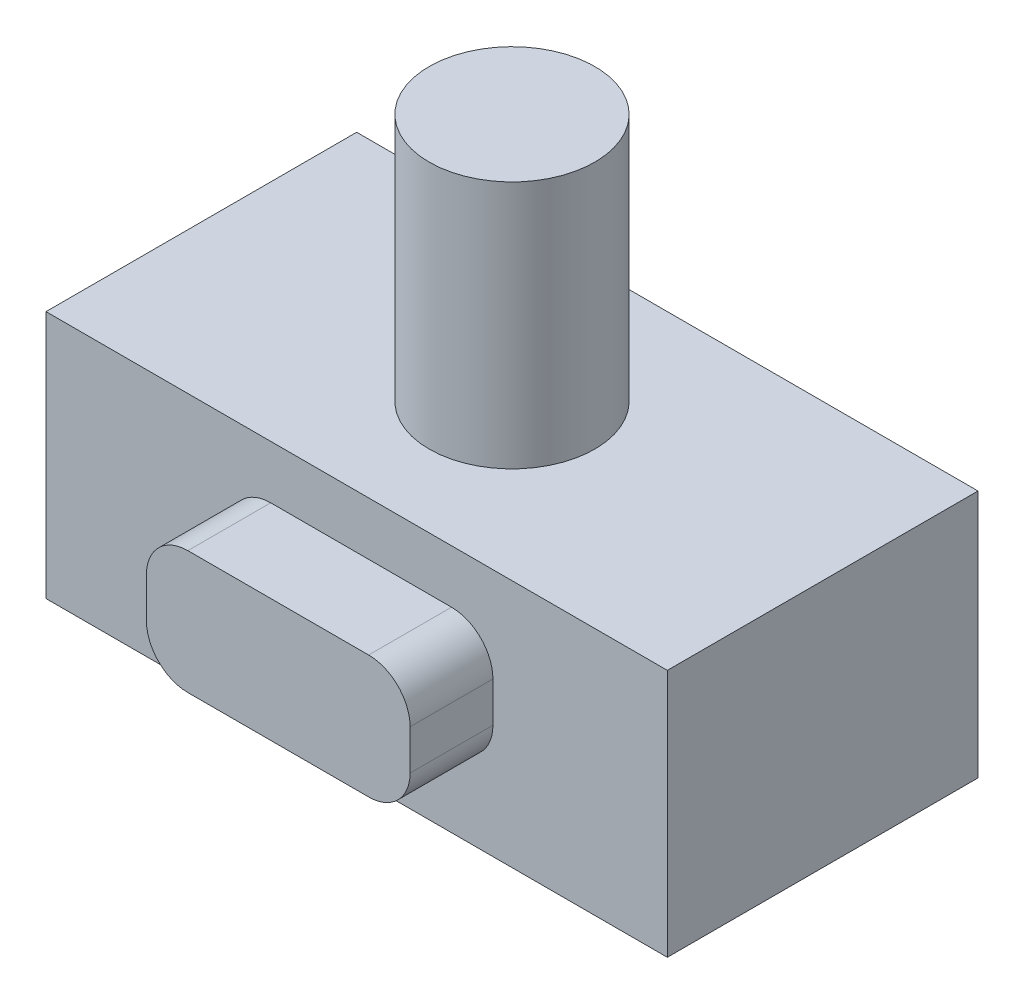
SolidWorks part; units mm, degrees
ref_plane "Front Plane" through (0, 0, 0) normal (0, 0, 1) x (1, 0, 0)
ref_plane "Top Plane" through (0, 0, 0) normal (0, 1, 0) x (1, 0, 0)
ref_plane "Right Plane" through (0, 0, 0) normal (1, 0, 0) x (0, 0, -1)
sketch "Sketch1" plane through (0, 0, 0) normal (0, 1, 0) x (1, 0, 0)
  line L1 (-75, -37.5) -> (75, -37.5)
  line L2 (-75, -37.5) -> (-75, 37.5)
  line L3 (-75, 37.5) -> (75, 37.5)
  line L4 (75, -37.5) -> (75, 37.5)
  line L5 (-75, -37.5) -> (75, 37.5) construction
  line L6 (-75, 37.5) -> (75, -37.5) construction
  point P0 (0, 0)
  dimension "D1" = 150
  dimension "D2" = 75
extrude "Boss-Extrude1" add sketch "Sketch1" along normal blind 60
sketch "Sketch2" plane through (0, 60, 0) normal (0, 1, 0) x (1, 0, 0)
  circle A0 centre (0, 0) radius 20
  dimension "D1" = 40
extrude "Boss-Extrude2" add sketch "Sketch2" along normal blind 60
sketch "Sketch3" plane through (0, 0, 37.5) normal (0, 0, 1) x (1, 0, 0)
  line L1 (-20.7503, 47.1503) -> (22.8957, 47.1503)
  line L2 (-30.7503, 37.1503) -> (-30.7503, 27.4727)
  line L3 (-20.7503, 17.4727) -> (22.8957, 17.4727)
  line L4 (32.8957, 37.1503) -> (32.8957, 27.4727)
  arc A0 (-30.7503, 27.4727) -> (-20.7503, 17.4727) centre (-20.7503, 27.4727) ccw
  arc A1 (22.8957, 17.4727) -> (32.8957, 27.4727) centre (22.8957, 27.4727) ccw
  arc A2 (32.8957, 37.1503) -> (22.8957, 47.1503) centre (22.8957, 37.1503) ccw
  arc A3 (-20.7503, 47.1503) -> (-30.7503, 37.1503) centre (-20.7503, 37.1503) ccw
  dimension "D1" = 10
extrude "Boss-Extrude3" add sketch "Sketch3" along normal blind 20
